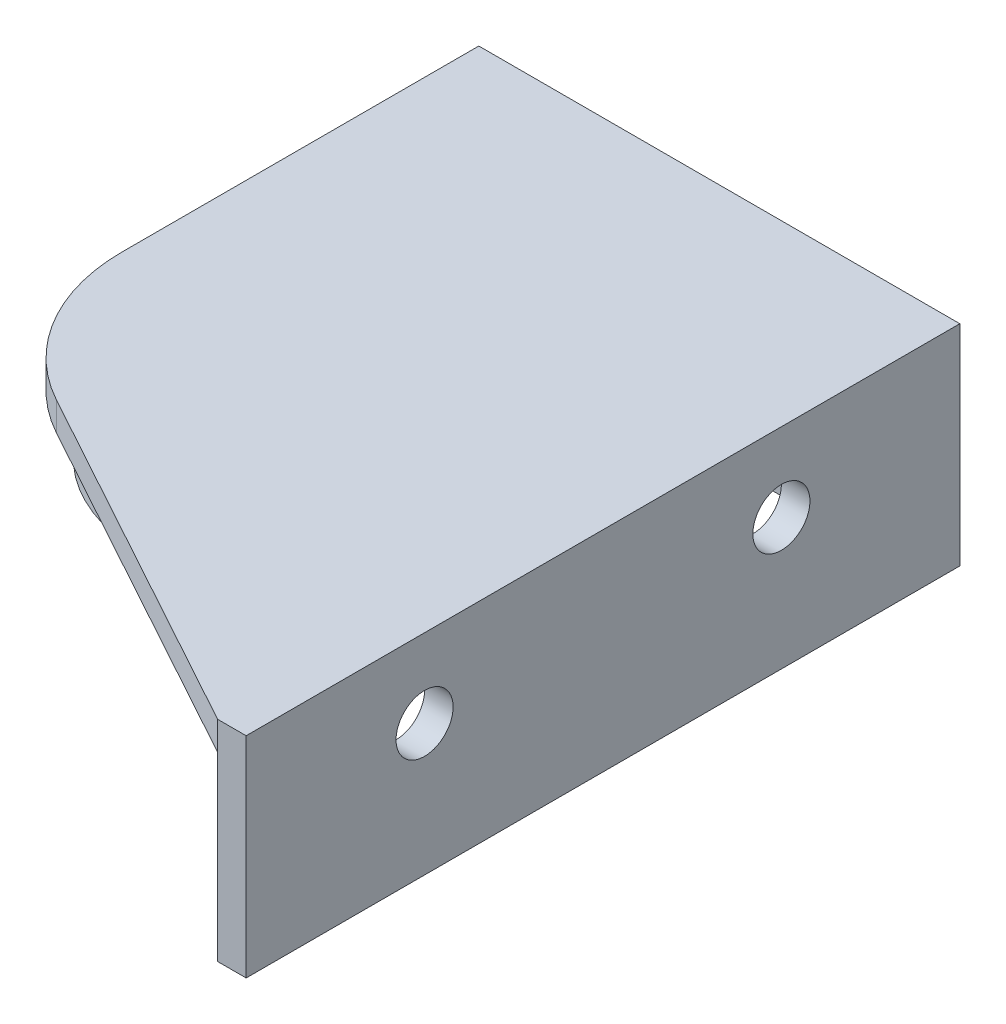
SolidWorks part; units mm, degrees
ref_plane "Front Plane" through (0, 0, 0) normal (0, 0, 1) x (1, 0, 0)
ref_plane "Top Plane" through (0, 0, 0) normal (0, 1, 0) x (1, 0, 0)
ref_plane "Right Plane" through (0, 0, 0) normal (1, 0, 0) x (0, 0, -1)
sketch "Sketch2" plane through (0, 0, 0) normal (0, 1, 0) x (1, 0, 0)
  line L1 (16.85, -25) -> (-16.85, -25)
  line L2 (16.85, -25) -> (16.85, 25)
  line L3 (16.85, 25) -> (-16.85, 25)
  line L4 (-16.85, -25) -> (-16.85, 25)
  line L5 (16.85, -25) -> (-16.85, 25) construction
  line L6 (16.85, 25) -> (-16.85, -25) construction
  point P0 (0, 0)
  dimension "D1" = 50
  dimension "D2" = 33.7
extrude "Boss-Extrude1" add sketch "Sketch2" along normal blind 2
sketch "Sketch3" plane through (0, 0, 0) normal (0, -1, 0) x (1, 0, 0)
  line L0 (14.85, 25) -> (14.85, -23)
  line L1 (-16.85, 25) -> (16.85, 25) construction
  line L2 (14.85, -23) -> (-16.85, -23)
  line L3 (-16.85, -23) -> (-16.85, -25)
  line L4 (-16.85, -25) -> (16.85, -25)
  line L5 (16.85, -25) -> (16.85, 25)
  line L6 (16.85, 25) -> (14.85, 25)
  dimension "D1" = 2
  dimension "D2" = 2
extrude "Boss-Extrude2" add sketch "Sketch3" along normal blind 12.7
sketch "Sketch4" plane through (16.85, 0, 0) normal (1, 0, 0) x (0, 0, -1)
  line L0 (-25, -3.5) -> (25, -3.5) construction
  line L1 (-25, 2) -> (-25, -12.7) construction
  line L2 (25, 2) -> (25, -12.7) construction
  line L3 (25, -12.7) -> (-25, -12.7) construction
  circle A0 centre (12.5, -3.5) radius 2
  circle A1 centre (-12.5, -3.5) radius 2
  dimension "D1" = 4
  dimension "D2" = 12.5
  dimension "D3" = 12.5
  dimension "D4" = 9.2
extrude "Cut-Extrude1" cut sketch "Sketch4" against normal up to next
sketch "Sketch5" plane through (0, 0, 0) normal (0, -1, 0) x (1, 0, 0)
  line L0 (-11.5, 0) -> (3.5, 0) construction
  circle A0 centre (-4, 0) radius 11.5
  circle A1 centre (-4, 0) radius 5.5
  point P3 (-4.043, -2.628)
  point P7 (-4, 0)
  point P8 (0, 0)
  dimension "D1" = 23
  dimension "D2" = 11
  dimension "D3" = 15
  dimension "D4" = 4
extrude "Boss-Extrude3" add sketch "Sketch5" along normal offset from surface (4.1 mm away) 8.6 up to face at (4.95, -12.7, -7.6667)
sketch "Sketch6" plane through (0, 2, 0) normal (0, 1, 0) x (1, 0, 0)
  line L0 (-16.85, 25) -> (-16.85, -25) construction
  line L1 (-10.1813, -11.2656) -> (14.85, -25)
  arc A0 (-16.85, 0) -> (-10.1813, -11.2656) centre (-4, 0) ccw
  circle A1 centre (-4, 0) radius 11.5 construction
extrude "Cut-Extrude-Thin1" cut sketch "Sketch6" against normal blind 8.2 and the other way through all thin
sketch "Sketch7" plane through (0, 0, -23) normal (0, 0, 1) x (1, 0, 0)
  line L0 (-16.85, -6.35) -> (14.85, -6.35) construction
  line L1 (-16.85, -12.7) -> (-16.85, 0) construction
  line L2 (14.85, -12.7) -> (14.85, 0) construction
  circle A0 centre (-9.85, -6.35) radius 2
  circle A1 centre (7.85, -6.35) radius 2
  dimension "D3" = 4
  dimension "D1" = 7
  dimension "D2" = 7
extrude "Cut-Extrude2" cut sketch "Sketch7" against normal up to next
